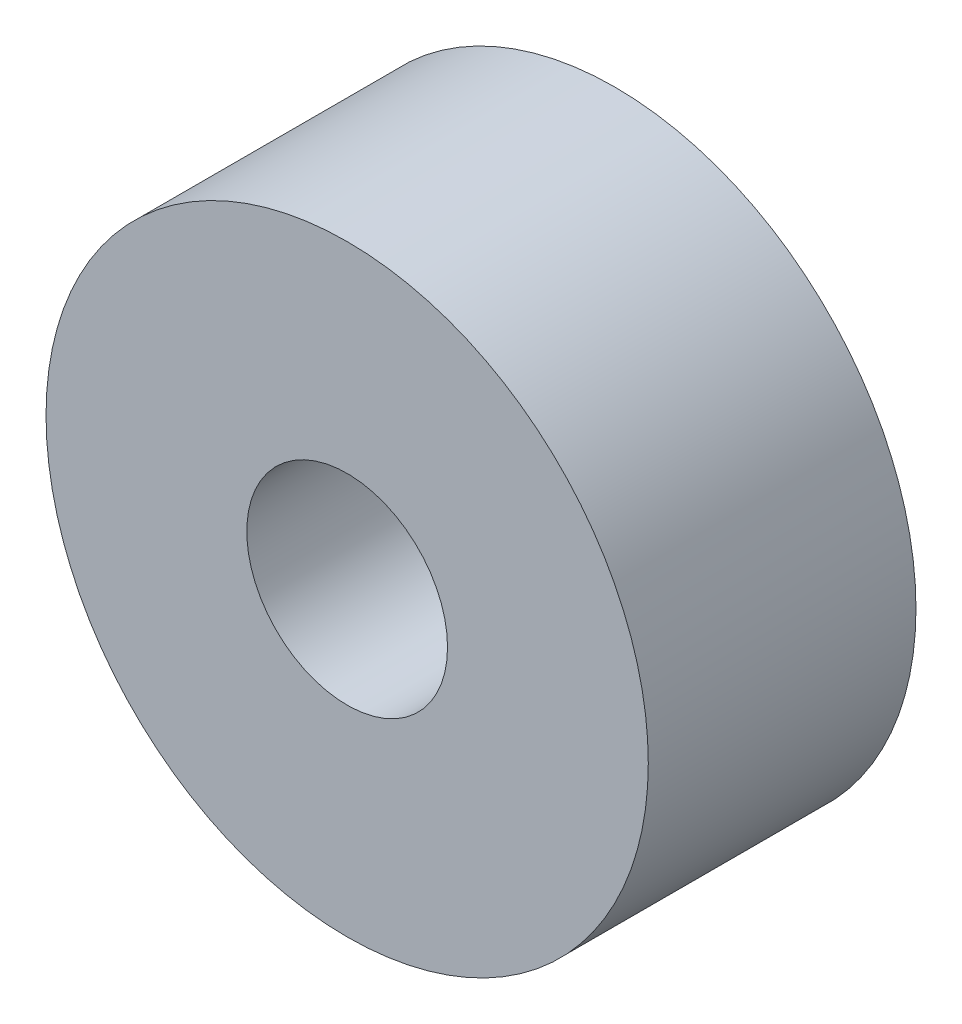
SolidWorks part; units mm, degrees
ref_plane "正面" through (0, 0, 0) normal (0, 0, 1) x (1, 0, 0)
ref_plane "平面" through (0, 0, 0) normal (0, 1, 0) x (1, 0, 0)
ref_plane "右側面" through (0, 0, 0) normal (1, 0, 0) x (0, 0, -1)
sketch "ｽｹｯﾁ1" plane through (0, 0, 0) normal (0, 0, 1) x (1, 0, 0)
  circle A0 centre (0, 0) radius 4.5
  circle A1 centre (0, 0) radius 1.5
  dimension "D1" = 9
  dimension "D2" = 3
extrude "ﾎﾞｽ - 押し出し1" add sketch "ｽｹｯﾁ1" along normal blind 4
